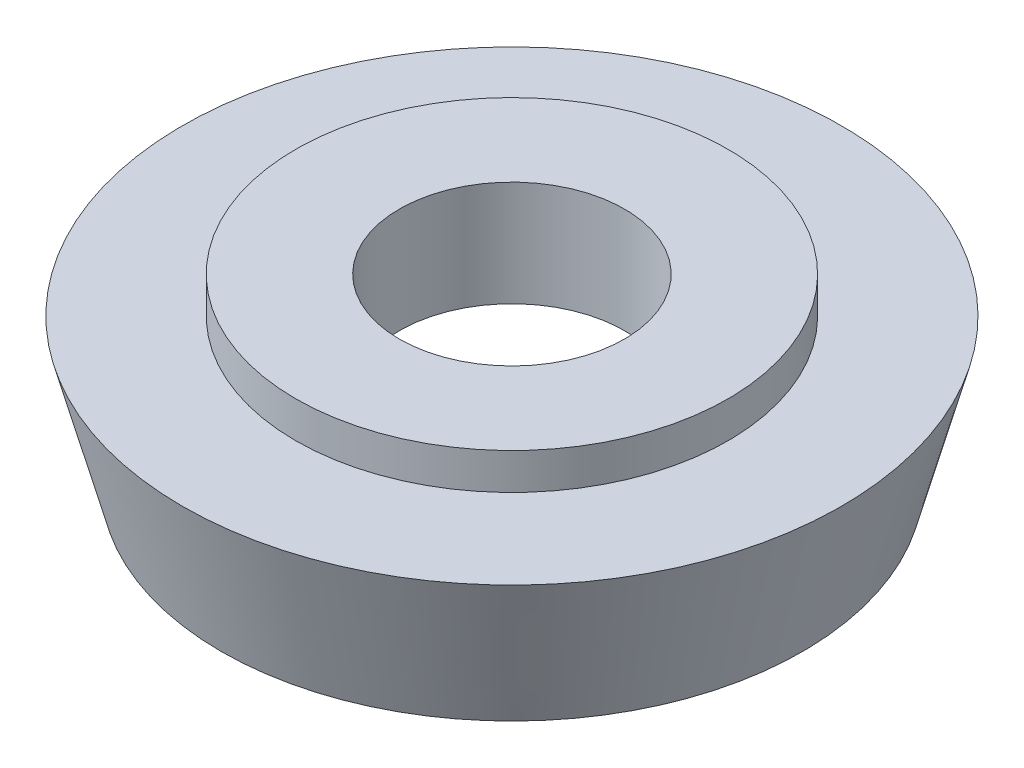
SolidWorks part; units mm, degrees
material "Delrin 2700 NC010, Low Viscosity Acetal Copolymer (SS)"
ref_plane "Front Plane" through (0, 0, 0) normal (0, 0, 1) x (1, 0, 0)
ref_plane "Top Plane" through (0, 0, 0) normal (0, 1, 0) x (1, 0, 0)
ref_plane "Right Plane" through (0, 0, 0) normal (1, 0, 0) x (0, 0, -1)
sketch "Sketch1" plane through (0, 0, 0) normal (0, 0, 1) x (1, 0, 0)
  line L0 (-1.55, 2.5) -> (-2.975, 2.5)
  line L1 (-2.975, 2.5) -> (-2.975, 2)
  line L2 (-2.975, 2) -> (-4.5359, 2)
  line L3 (-4.5359, 2) -> (-4, 0)
  line L4 (-4, 0) -> (-3.05, 0)
  line L5 (-3.05, 0) -> (-3.05, 1.05)
  line L6 (-3.05, 1.05) -> (-1.55, 1.05)
  line L7 (-1.55, 1.05) -> (-1.55, 2.5)
  line L8 (0, 2.5) -> (0, 0) construction
  dimension "D1" = 2.5
  dimension "D2" = 3.1
  dimension "D3" = 6.1
  dimension "D4" = 5.95
  dimension "D5" = 15
  dimension "D6" = 2
  dimension "D7" = 1.05
  dimension "D8" = 8
revolve "Revolve1" add sketch "Sketch1" angle 360 about L8
